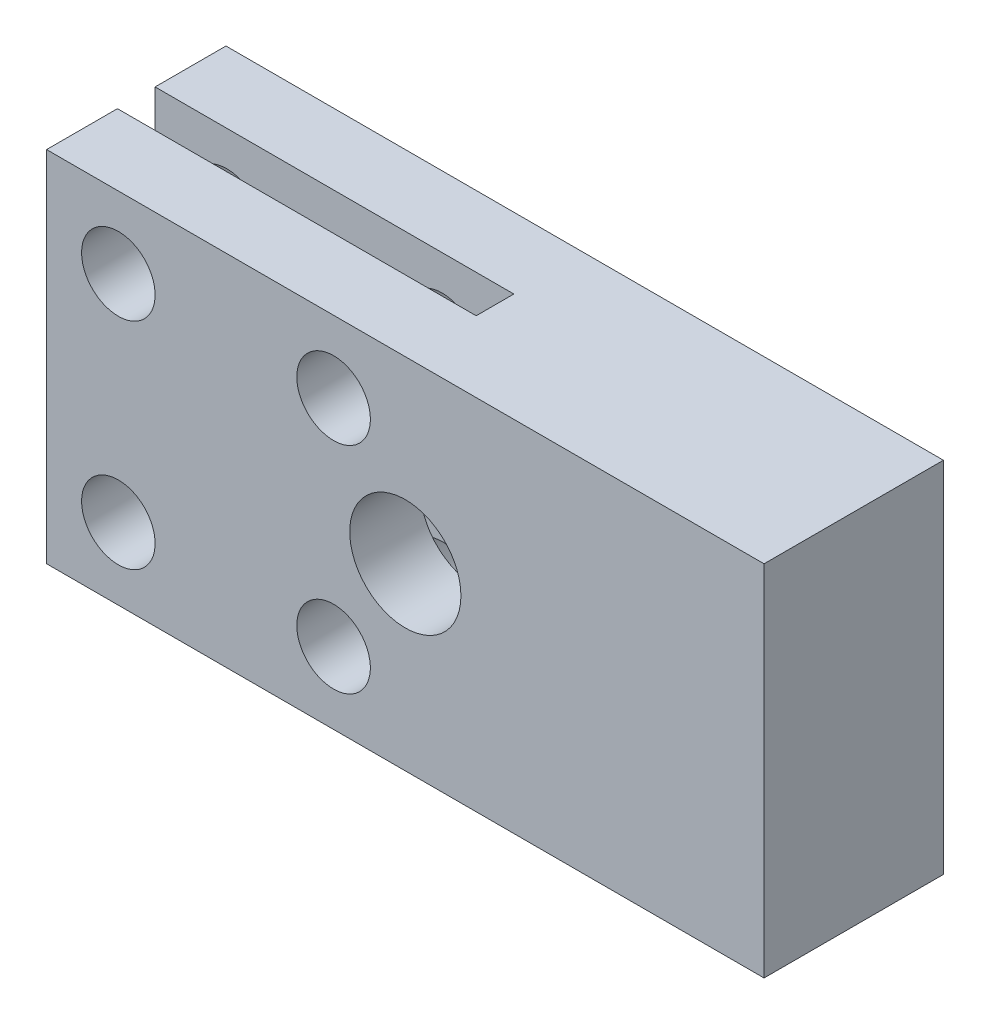
SolidWorks part; units mm, degrees
ref_plane "Plan de face" through (0, 0, 0) normal (0, 0, 1) x (1, 0, 0)
ref_plane "Plan de dessus" through (0, 0, 0) normal (0, 1, 0) x (1, 0, 0)
ref_plane "Plan de droite" through (0, 0, 0) normal (1, 0, 0) x (0, 0, -1)
sketch "Esquisse1" plane through (0, 0, 0) normal (0, 0, 1) x (1, 0, 0)
  line L1 (20, 10) -> (-20, 10)
  line L2 (20, 10) -> (20, -10)
  line L3 (20, -10) -> (-20, -10)
  line L4 (-20, 10) -> (-20, -10)
  line L5 (20, 10) -> (-20, -10) construction
  line L6 (20, -10) -> (-20, 10) construction
  point P0 (0, 0)
  dimension "D1" = 40
  dimension "D2" = 20
extrude "Boss.-Extru.1" add sketch "Esquisse1" along normal blind 10
sketch "Esquisse2" plane through (0, 0, 10) normal (0, 0, 1) x (1, 0, 0)
  circle A0 centre (0, 0) radius 3.1
  dimension "D1" = 6.2
extrude "Enlèv. mat.-Extru.1" cut sketch "Esquisse2" against normal blind 10
sketch "Esquisse3" plane through (0, -10, 0) normal (0, -1, 0) x (-1, 0, 0)
  line L0 (20, -10) -> (20, 0) construction
  line L1 (40, -6.05) -> (0, -6.05)
  line L2 (40, -6.05) -> (40, -3.95)
  line L3 (40, -3.95) -> (0, -3.95)
  line L4 (0, -6.05) -> (0, -3.95)
  line L5 (40, -6.05) -> (0, -3.95) construction
  line L6 (40, -3.95) -> (0, -6.05) construction
  point P0 (20, -5)
  dimension "D1" = 2.1
  dimension "D2" = 20
extrude "Enlèv. mat.-Extru.2" cut sketch "Esquisse3" against normal through all
sketch "Esquisse4" plane through (0, 0, 0) normal (0, 0, -1) x (-1, 0, 0)
  line L0 (-20, 10) -> (20, 10) construction
  line L1 (20, 10) -> (20, -10) construction
  line L2 (0, 10) -> (0, 3.1) construction
  line L3 (20, -10) -> (-20, -10) construction
  circle A0 centre (16, 6) radius 2.05
  circle A1 centre (4, 6) radius 2.05
  circle A2 centre (4, -6) radius 2.05
  circle A3 centre (16, -6) radius 2.05
  dimension "D1" = 4.1
  dimension "D2" = 4
  dimension "D3" = 4
  dimension "D4" = 4
  dimension "D5" = 4
extrude "Enlèv. mat.-Extru.3" cut sketch "Esquisse4" against normal through all
